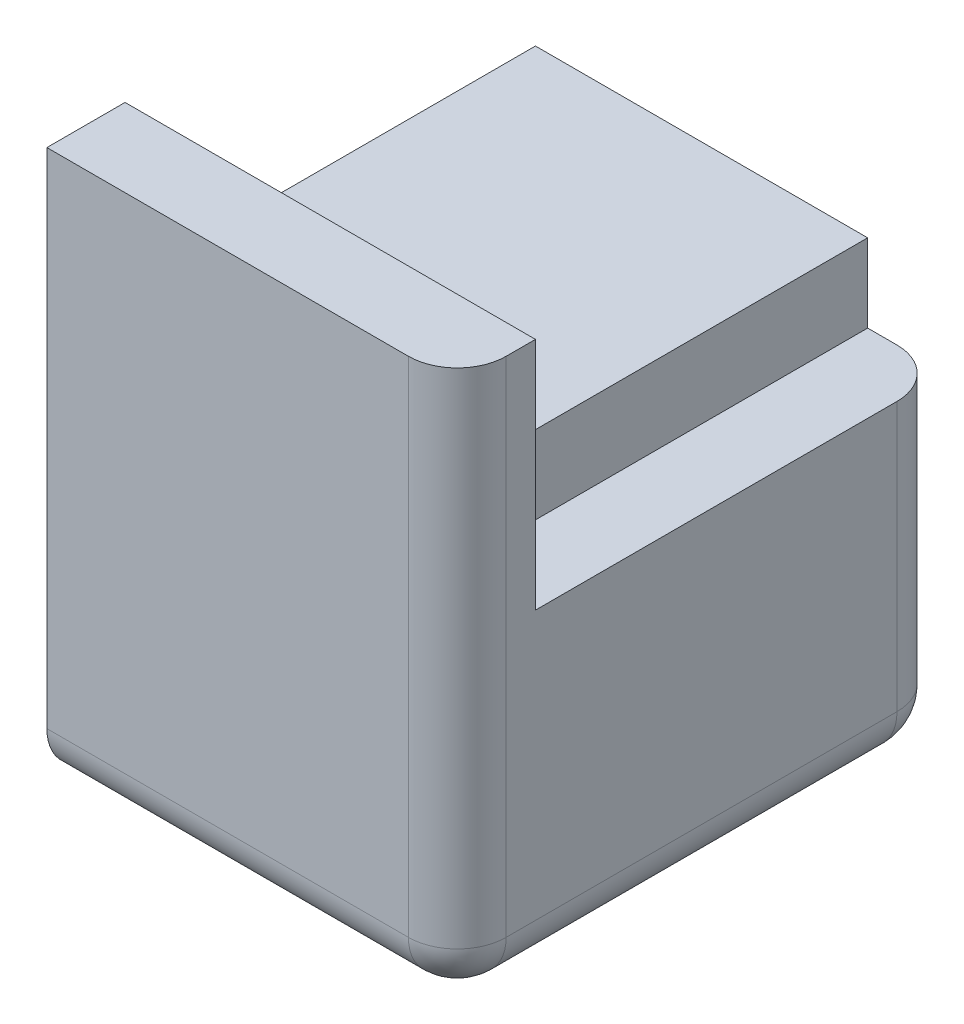
SolidWorks part; units mm, degrees
ref_plane "Front Plane" through (0, 0, 0) normal (0, 0, 1) x (1, 0, 0)
ref_plane "Top Plane" through (0, 0, 0) normal (0, 1, 0) x (1, 0, 0)
ref_plane "Right Plane" through (0, 0, 0) normal (1, 0, 0) x (0, 0, -1)
sketch "Sketch2" plane through (0, 0, 0) normal (0, 1, 0) x (1, 0, 0)
  line L1 (-4.2, -5) -> (4.2, -5)
  line L2 (-4.2, -5) -> (-4.2, 5)
  line L3 (-4.2, 5) -> (4.2, 5)
  line L4 (4.2, -5) -> (4.2, 5)
  line L5 (-4.2, -5) -> (4.2, 5) construction
  line L6 (-4.2, 5) -> (4.2, -5) construction
  point P0 (0, 0)
extrude "Boss-Extrude1" add sketch "Sketch2" along normal blind 11.3
sketch "Sketch5" plane through (4.2, 0, 0) normal (1, 0, 0) x (0, 0, -1)
  line L0 (-5, 11.3) -> (-5, 0) construction
  line L1 (5, 11.3) -> (-3.4, 11.3)
  line L2 (5, 11.3) -> (5, 9.8)
  line L3 (5, 9.8) -> (-3.4, 9.8)
  line L4 (-3.4, 11.3) -> (-3.4, 9.8)
  dimension "D1" = 1.6
  dimension "D2" = 1.5
extrude "Cut-Extrude2" cut sketch "Sketch5" against normal blind 11.3
sketch "Sketch7" plane through (0, 0, -5) normal (0, 0, -1) x (-1, 0, 0)
  line L1 (-4.2, 9.8) -> (-2.6, 9.8)
  line L2 (-4.2, 9.8) -> (-4.2, 6.5)
  line L3 (-4.2, 6.5) -> (-2.6, 6.5)
  line L4 (-2.6, 9.8) -> (-2.6, 6.5)
  dimension "D1" = 1.6
  dimension "D2" = 3.3
extrude "Cut-Extrude4" cut sketch "Sketch7" against normal up to vertex (8.4 mm away)
sketch "Sketch9" plane through (2.6, 0, 0) normal (1, 0, 0) x (0, 0, -1)
  line L0 (5, 6.5) -> (5, 9.8) construction
  line L1 (-3.4, 9.8) -> (5, 9.8)
  line L2 (-3.4, 9.8) -> (-3.4, 8.1)
  line L3 (-3.4, 8.1) -> (5, 8.1)
  line L4 (5, 9.8) -> (5, 8.1)
  line L5 (-3.4, 6.5) -> (5, 6.5) construction
  dimension "D1" = 1.6
extrude "Cut-Extrude5" cut sketch "Sketch9" against normal blind 6.8
sketch "Sketch12" plane through (0, 0, 3.4) normal (0, 0, -1) x (-1, 0, 0)
  line L0 (4.2, 11.3) -> (4.2, 8.1) construction
  line L1 (-2.6, 8.1) -> (4.2, 8.1)
  line L2 (-2.6, 8.1) -> (-2.6, 9.7)
  line L3 (-2.6, 9.7) -> (4.2, 9.7)
  line L4 (4.2, 8.1) -> (4.2, 9.7)
extrude "Boss-Extrude3" add sketch "Sketch12" along normal blind 1.6
fillet "Fillet1" radius 1 5 edges at (0, 0, 5) (4.2, 5.65, 5) (4.2, 3.25, -5) (0, 0, -5) (4.2, 0, 0)
hole_wizard "M3x0.5 Tapped Hole2" positions "Sketch16" profile "Sketch15" tap size "M3x0.5" standard "ANSI Metric"
sketch "Sketch16" plane through (-4.2, 0, 0) normal (-1, 0, 0) x (0, 0, 1)
  line L0 (-4, 0) -> (4, 0) construction
  point P0 (0, 5)
  dimension "D1" = 5
sketch "Sketch15" plane through (-4.2, 5, 0) normal (0, 1, 0) x (0, 0, 1)
  line L0 (0, 0) -> (0, 7.2511)
  line L1 (0, 7.2511) -> (1.25, 6.5)
  line L2 (1.25, 6.5) -> (1.25, 0)
  line L5 (1.25, 0) -> (0, 0)
  line L10 (0, 7.2511) -> (-1.25, 6.5) construction
  line L11 (0, -6.35) -> (0, 107.95) construction
  dimension "Tap Drill Dia." = 2.5
  dimension "Tap Drill Depth" = 6.5
  dimension "Drill Angle" = 118
cosmetic thread "Hole Thread2" parameters "D1"=5, "D2"=3
